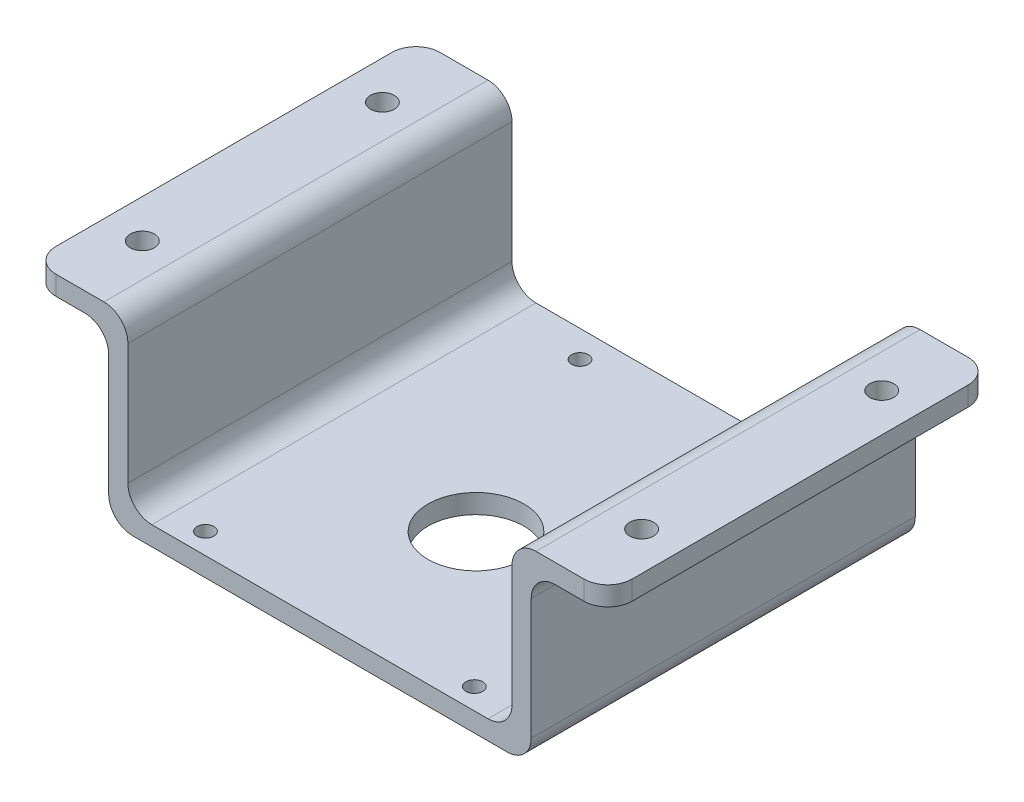
SolidWorks part; units mm, degrees
ref_plane "Front Plane" through (0, 0, 0) normal (0, 0, 1) x (1, 0, 0)
ref_plane "Top Plane" through (0, 0, 0) normal (0, 1, 0) x (1, 0, 0)
ref_plane "Right Plane" through (0, 0, 0) normal (1, 0, 0) x (0, 0, -1)
sketch "Sketch2" plane through (0, 0, 0) normal (0, 1, 0) x (1, 0, 0)
  line L1 (40, -40) -> (-40, -40)
  line L2 (40, -40) -> (40, 40)
  line L3 (40, 40) -> (-40, 40)
  line L4 (-40, -40) -> (-40, 40)
  line L5 (40, -40) -> (-40, 40) construction
  line L6 (40, 40) -> (-40, -40) construction
  point P0 (0, 0)
  dimension "D1" = 80
extrude "Boss-Extrude1" add sketch "Sketch2" along normal blind 4
sketch "Sketch3" plane through (0, 4, 0) normal (0, 1, 0) x (1, 0, 0)
  line L0 (40, 40) -> (-40, 40) construction
  circle A0 centre (0, -7.5) radius 10
  dimension "D1" = 47.5
extrude "Cut-Extrude1" cut sketch "Sketch3" against normal blind 4
sketch "Sketch4" plane through (0, 4, 0) normal (0, 1, 0) x (1, 0, 0)
  circle A0 centre (-28.2319, -35.6122) radius 1.75
  circle A1 centre (27.7681, -35.6122) radius 1.75
  circle A3 centre (19.7681, 34.3878) radius 1.75
  circle A4 centre (-20.2319, 34.3878) radius 1.75
extrude "Cut-Extrude2" cut sketch "Sketch4" against normal blind 10
sketch "Sketch7" plane through (-40, 0, 0) normal (-1, 0, 0) x (0, 0, 1)
  line L0 (40, 4) -> (40, 0) construction
  line L1 (-40, 0) -> (40, 0)
  line L2 (-40, 0) -> (-40, 39.2)
  line L3 (-40, 39.2) -> (40, 39.2)
  line L4 (40, 0) -> (40, 39.2)
  dimension "D1" = 0
  dimension "D2" = 39.2
extrude "Boss-Extrude3" add sketch "Sketch7" along normal blind 4
mirror "Mirror2" about plane through (0, 0, 0) normal (1, 0, 0) of "Boss-Extrude3"
sketch "Sketch8" plane through (0, 39.2, 0) normal (0, 1, 0) x (1, 0, 0)
  line L0 (-44, -40) -> (-40, -40) construction
  line L1 (-40, 40) -> (-60, 40)
  line L2 (-40, 40) -> (-40, -40)
  line L3 (-40, -40) -> (-60, -40)
  line L4 (-60, 40) -> (-60, -40)
  dimension "D1" = 0
  dimension "D2" = 20
extrude "Boss-Extrude4" add sketch "Sketch8" against normal blind 4
mirror "Mirror3" about plane through (0, 0, 0) normal (1, 0, 0) of "Boss-Extrude4"
sketch "Sketch9" plane through (0, 39.2, 0) normal (0, 1, 0) x (1, 0, 0)
  line L0 (-60, -40) -> (-44, -40) construction
  line L1 (-21.56, 0) -> (21.56, 0) construction
  line L2 (0, -21.56) -> (0, 21.56) construction
  circle A0 centre (-52, -25) radius 2.5
  circle A1 centre (-52, 25) radius 2.5
  circle A2 centre (52, 25) radius 2.5
  circle A3 centre (52, -25) radius 2.5
  dimension "D1" = 15
extrude "Cut-Extrude3" cut sketch "Sketch9" against normal blind 4
fillet "Fillet1" radius 5 12 edges at (-44, 35.2, 0) (44, 35.2, 0) (40, 39.2, 0) (-40, 39.2, 0) (-44, 0, 0) (44, 0, 0) (40, 4, 0) (-40, 4, 0) (60, 37.2, 40) (60, 37.2, -40) (-60, 37.2, -40) (-60, 37.2, 40)
